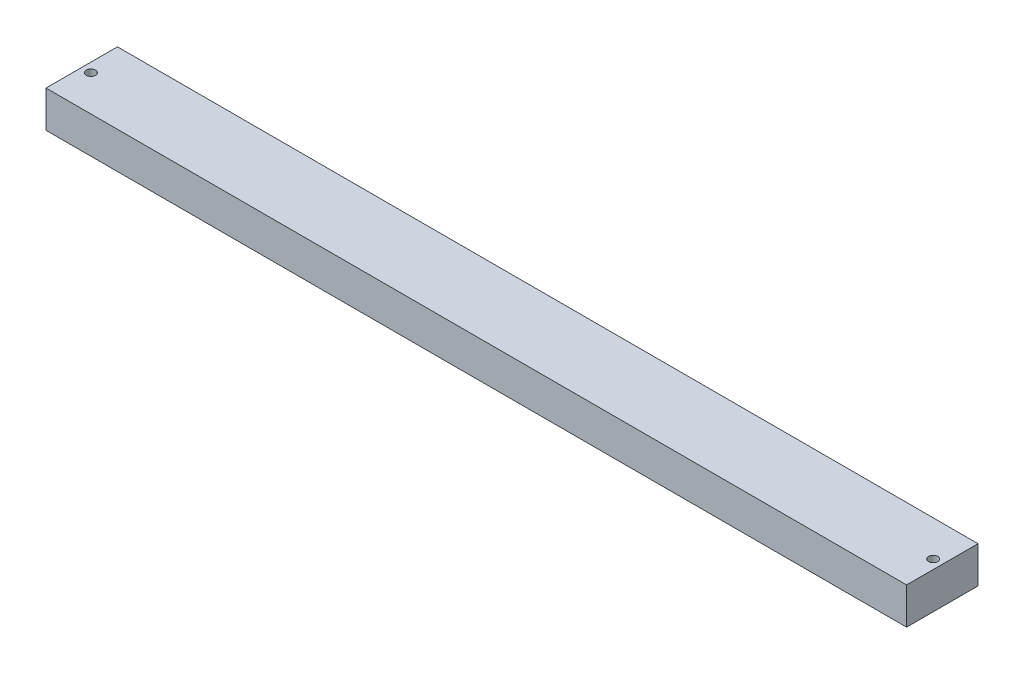
SolidWorks part; units mm, degrees
material "1023 Carbon Steel Sheet (SS)"
ref_plane "Front Plane" through (0, 0, 0) normal (0, 0, 1) x (1, 0, 0)
ref_plane "Top Plane" through (0, 0, 0) normal (0, 1, 0) x (1, 0, 0)
ref_plane "Right Plane" through (0, 0, 0) normal (1, 0, 0) x (0, 0, -1)
sketch "Sketch1" plane through (0, 0, 0) normal (0, 0, 1) x (1, 0, 0)
  line L1 (235, -10) -> (-235, -10)
  line L2 (235, -10) -> (235, 10)
  line L3 (235, 10) -> (-235, 10)
  line L4 (-235, -10) -> (-235, 10)
  line L5 (235, -10) -> (-235, 10) construction
  line L6 (235, 10) -> (-235, -10) construction
  point P0 (0, 0)
  dimension "D1" = 470
  dimension "D2" = 20
extrude "Boss-Extrude1" add sketch "Sketch1" along normal mid plane 39
sketch "Sketch2" plane through (0, 10, 0) normal (0, 1, 0) x (1, 0, 0)
  line L0 (-235, -19.5) -> (-235, 19.5) construction
  circle A0 centre (-175, 0) radius 10
  dimension "D1" = 20
  dimension "D2" = 60
extrude "Cut-Extrude1" cut sketch "Sketch2" against normal blind 28
pattern_linear "LPattern1" count 8 spacing 50 along (1, 0, 0) of "Cut-Extrude1"
sketch "Sketch3" plane through (0, 10, 0) normal (0, 1, 0) x (1, 0, 0)
  line L0 (235, -19.5) -> (-235, -19.5) construction
  line L1 (235, -19.5) -> (235, 19.5) construction
  circle A0 centre (230, 0) radius 2.5
  dimension "D1" = 5
  dimension "D2" = 19.5
  dimension "D3" = 5
extrude "Cut-Extrude2" cut sketch "Sketch3" against normal blind 42
mirror "Mirror1" about plane through (0, 0, 0) normal (1, 0, 0) of "Cut-Extrude2"
sketch "Sketch4" plane through (0, 10, 0) normal (0, 1, 0) x (1, 0, 0)
  circle A0 centre (-175, 0) radius 10 construction
  circle A1 centre (-125, 0) radius 10 construction
  circle A2 centre (-75, 0) radius 10 construction
  circle A3 centre (-25, 0) radius 10 construction
  circle A4 centre (25, 0) radius 10 construction
  circle A5 centre (75, 0) radius 10 construction
  circle A6 centre (125, 0) radius 10 construction
  circle A7 centre (175, 0) radius 10 construction
  circle A8 centre (-175, 0) radius 10
  circle A9 centre (-125, 0) radius 10
  circle A10 centre (-75, 0) radius 10
  circle A11 centre (-25, 0) radius 10
  circle A12 centre (25, 0) radius 10
  circle A13 centre (75, 0) radius 10
  circle A14 centre (125, 0) radius 10
  circle A15 centre (175, 0) radius 10
extrude "Boss-Extrude2" add sketch "Sketch4" against normal blind 4.8
sketch "Sketch5" plane through (-235, 0, 0) normal (-1, 0, 0) x (0, 0, 1)
  line L0 (19.5, 10) -> (-19.5, 10) construction
  line L1 (-19.5, 10) -> (-19.5, -10) construction
  circle A4 centre (-12.5, 6) radius 1.5
  circle A5 centre (-12.5, -6) radius 1.5
  circle A6 centre (9.5, 6) radius 1.5
  circle A7 centre (9.5, -6) radius 1.5
  dimension "D3" = 3
  dimension "D6" = 3
  dimension "D1" = 4
  dimension "D2" = 7
  dimension "D4" = 12
  dimension "D5" = 22
extrude "Cut-Extrude3" cut sketch "Sketch5" against normal blind 10
